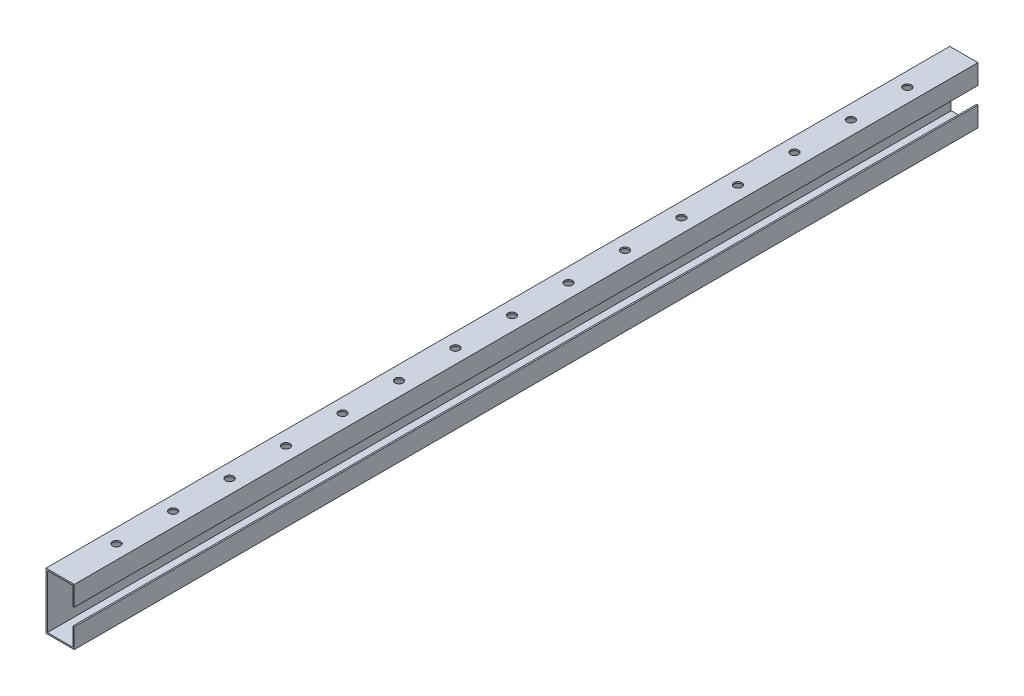
SolidWorks part; units mm, degrees
material "AISI 1020 Acero laminado en frío"
ref_plane "Alzado" through (0, 0, 0) normal (0, 0, 1) x (1, 0, 0)
ref_plane "Planta" through (0, 0, 0) normal (0, 1, 0) x (1, 0, 0)
ref_plane "Vista lateral" through (0, 0, 0) normal (1, 0, 0) x (0, 0, -1)
sketch "Croquis1" plane through (0, 0, 0) normal (0, 0, 1) x (1, 0, 0)
  line L0 (-22.5, -47.5) -> (-22.5, 47.5)
  line L1 (-25, -50) -> (25, -50)
  line L2 (-25, -50) -> (-25, 50)
  line L3 (-25, 50) -> (25, 50)
  line L4 (25, -50) -> (25, 50)
  line L5 (-25, -50) -> (25, 50) construction
  line L6 (-25, 50) -> (25, -50) construction
  line L7 (-22.5, 47.5) -> (22.5, 47.5)
  line L8 (22.5, -47.5) -> (22.5, 47.5)
  line L9 (-22.5, -47.5) -> (22.5, -47.5)
  point P0 (0, 0)
  dimension "D1" = 100
  dimension "D2" = 50
  dimension "D3" = 2.5
extrude "Saliente-Extruir1" add sketch "Croquis1" along normal mid plane 1600
sketch "Croquis2" plane through (25, 0, 0) normal (1, 0, 0) x (0, 0, -1)
  line L1 (800, 15) -> (-800, 15)
  line L2 (800, 15) -> (800, -15)
  line L3 (800, -15) -> (-800, -15)
  line L4 (-800, 15) -> (-800, -15)
  line L5 (800, 15) -> (-800, -15) construction
  line L6 (800, -15) -> (-800, 15) construction
  point P0 (0, 0)
  dimension "D1" = 1600
  dimension "D2" = 30
extrude "Cortar-Extruir1" cut sketch "Croquis2" against normal blind 5
sketch "Croquis8" plane through (25, 50, 0) normal (0, -1, 0) x (0, 0, 1)
  line L0 (850.2048, 25) -> (-1024.1629, 25) construction
  line L1 (0, 25) -> (100, 25) construction
  line L2 (0, 25) -> (-100, 25) construction
  circle A0 centre (0, 25) radius 7.1437
  circle A1 centre (100, 25) radius 7.1438
  circle A2 centre (200, 25) radius 7.1437
  circle A3 centre (300, 25) radius 7.1438
  circle A4 centre (400, 25) radius 7.1438
  circle A5 centre (500, 25) radius 7.1437
  circle A6 centre (600, 25) radius 7.1437
  circle A7 centre (700, 25) radius 7.1437
  circle A8 centre (-100, 25) radius 7.1438
  circle A9 centre (-200, 25) radius 7.1437
  circle A10 centre (-300, 25) radius 7.1438
  circle A11 centre (-400, 25) radius 7.1438
  circle A12 centre (-500, 25) radius 7.1438
  circle A13 centre (-600, 25) radius 7.1437
  circle A14 centre (-700, 25) radius 7.1437
  dimension "D1" = 14.2875
  dimension "D3" = 100
  dimension "D5" = 100
  dimension "D2" = 8
  dimension "D4" = 8
extrude "Cortar-Extruir2" cut sketch "Croquis8" along normal blind 130
